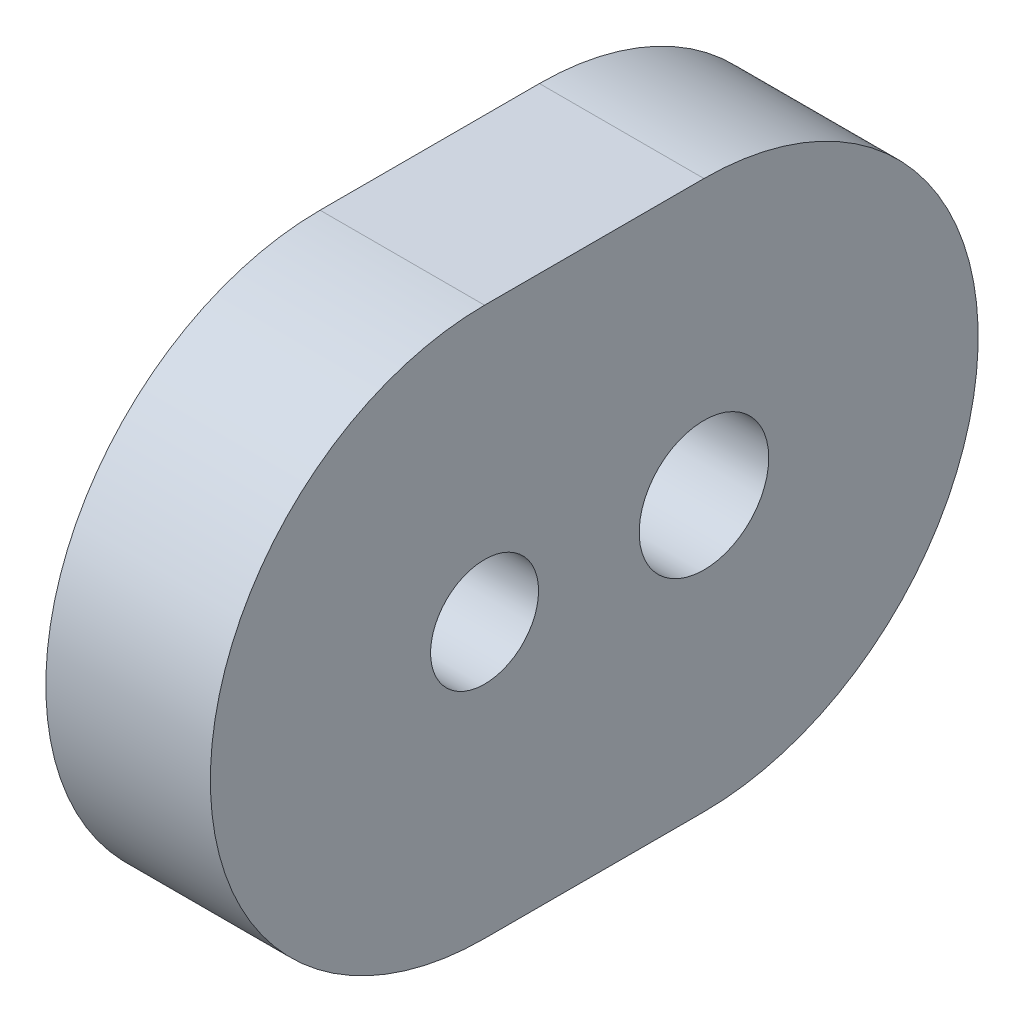
SolidWorks part; units mm, degrees
ref_plane "Front Plane" through (0, 0, 0) normal (0, 0, 1) x (1, 0, 0)
ref_plane "Top Plane" through (0, 0, 0) normal (0, 1, 0) x (1, 0, 0)
ref_plane "Right Plane" through (0, 0, 0) normal (1, 0, 0) x (0, 0, -1)
sketch "Sketch1" plane through (0, 0, 0) normal (1, 0, 0) x (0, 0, -1)
  line L1 (0, 0) -> (5.08, 0)
  line L3 (0, 12.7) -> (5.08, 12.7)
  arc A0 (0, 12.7) -> (0, 0) centre (0, 6.35) ccw
  arc A1 (5.08, 12.7) -> (5.08, 0) centre (5.08, 6.35) cw
  dimension "D1" = 12.7
  dimension "D2" = 5.08
extrude "Boss-Extrude1" add sketch "Sketch1" along normal blind 3.81
hole_wizard "Tap Drill for M3 Tap1" positions "Sketch3" profile "Sketch2" hole size "M3" standard "ISO" end condition through all
sketch "Sketch3" plane through (3.81, 0, 0) normal (1, 0, 0) x (0, 0, -1)
  point P0 (0, 6.35)
sketch "Sketch2" plane through (3.81, 6.35, 0) normal (0, 1, 0) x (0, 0, -1)
  line L0 (0, 0) -> (0, 3.81)
  line L1 (0, 3.81) -> (1.25, 3.81)
  line L2 (1.25, 3.81) -> (1.25, 0)
  line L5 (1.25, 0) -> (0, 0)
  line L11 (0, -6.35) -> (0, 107.95) construction
  dimension "Thru Hole Dia." = 2.5
  dimension "Thru Hole Depth" = 3.81
hole_wizard "Ø3.0mm Dowel Hole1" positions "Sketch5" profile "Sketch4" hole size "Ø3.0" standard "ISO" end condition through all
sketch "Sketch5" plane through (3.81, 0, 0) normal (1, 0, 0) x (0, 0, -1)
  point P0 (5.08, 6.35)
sketch "Sketch4" plane through (3.81, 6.35, -5.08) normal (0, 1, 0) x (0, 0, -1)
  line L0 (0, 0) -> (0, 3.81)
  line L1 (0, 3.81) -> (1.5, 3.81)
  line L2 (1.5, 3.81) -> (1.5, 0)
  line L5 (1.5, 0) -> (0, 0)
  line L11 (0, -6.35) -> (0, 107.95) construction
  dimension "Thru Hole Dia." = 3
  dimension "Thru Hole Depth" = 3.81
